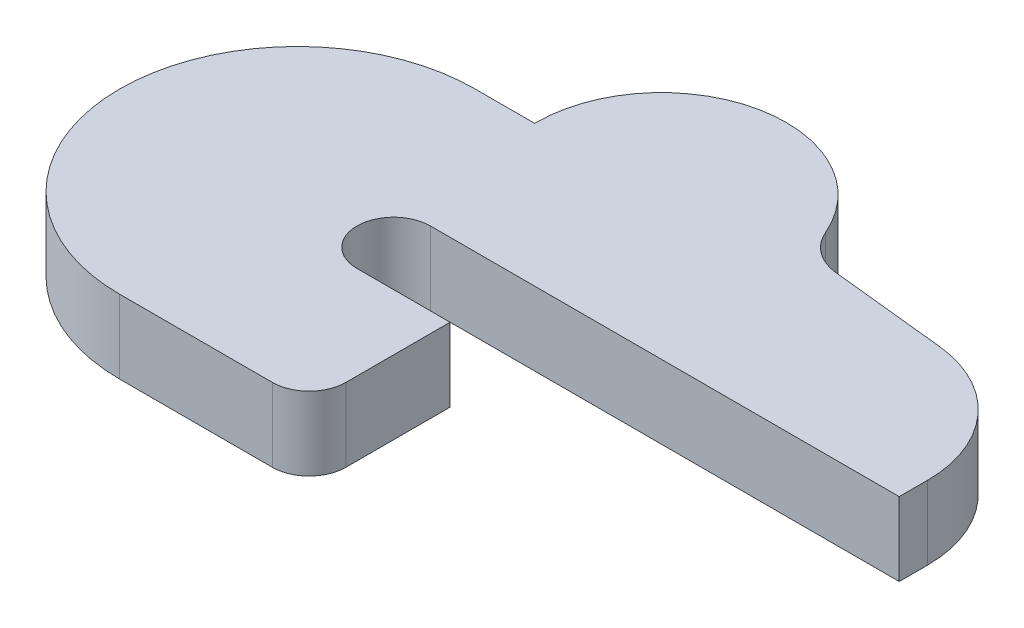
SolidWorks part; units mm, degrees
ref_plane "Front Plane" through (0, 0, 0) normal (0, 0, 1) x (1, 0, 0)
ref_plane "Top Plane" through (0, 0, 0) normal (0, 1, 0) x (1, 0, 0)
ref_plane "Right Plane" through (0, 0, 0) normal (1, 0, 0) x (0, 0, -1)
sketch "Sketch1" plane through (0, 0, 0) normal (0, 1, 0) x (1, 0, 0)
  line L0 (0, 0) -> (-3.8, 0)
  line L1 (-3.8, 3) -> (15.32, 3)
  line L2 (15.32, 3) -> (15.32, 4.1514)
  line L6 (-5.3, 8.8141) -> (-5.3, 8.75)
  line L7 (-5.3, 8.75) -> (-7.73, 8.75)
  line L9 (0, -4.25) -> (0, 0)
  line L10 (-7.73, -5.75) -> (-1.5, -5.75)
  line L11 (6.1174, 9.6206) -> (10.8426, 9.124)
  arc A0 (-3.8, 0) -> (-3.8, 3) centre (-3.8, 1.5) cw
  arc A5 (-7.73, 8.75) -> (-7.73, -5.75) centre (-7.73, 1.5) ccw
  arc A10 (-1.5, -5.75) -> (0, -4.25) centre (-1.5, -4.25) ccw
  arc A11 (-5.3, 8.8141) -> (4.488, 10.8222) centre (-0.2, 8.8141) cw
  arc A12 (4.488, 10.8222) -> (6.1174, 9.6206) centre (6.3265, 11.6097) ccw
  arc A13 (15.32, 4.1514) -> (10.8426, 9.124) centre (10.32, 4.1514) ccw
  point P10 (-1.225, 13.81)
  point P15 (4.8119, 9.7578)
  point P17 (5.1394, 10)
  point P19 (-14.98, 1.5)
  point P44 (-5.3, 1.5)
  dimension "10.9" = 7.25
  dimension "D4" = 1.5
  dimension "D5" = 19.56
  dimension "D6" = 6
  dimension "D7" = 2
  dimension "D10" = 30.3
  dimension "D11" = 1.5
  dimension "D2" = 5.1
  dimension "D8" = 5
  dimension "13.48" = 19.12
  dimension "80" = 90
  dimension "D9" = 3.8
  dimension "D37" = 7
extrude "Boss-Extrude2" add sketch "Sketch1" along normal blind 3
